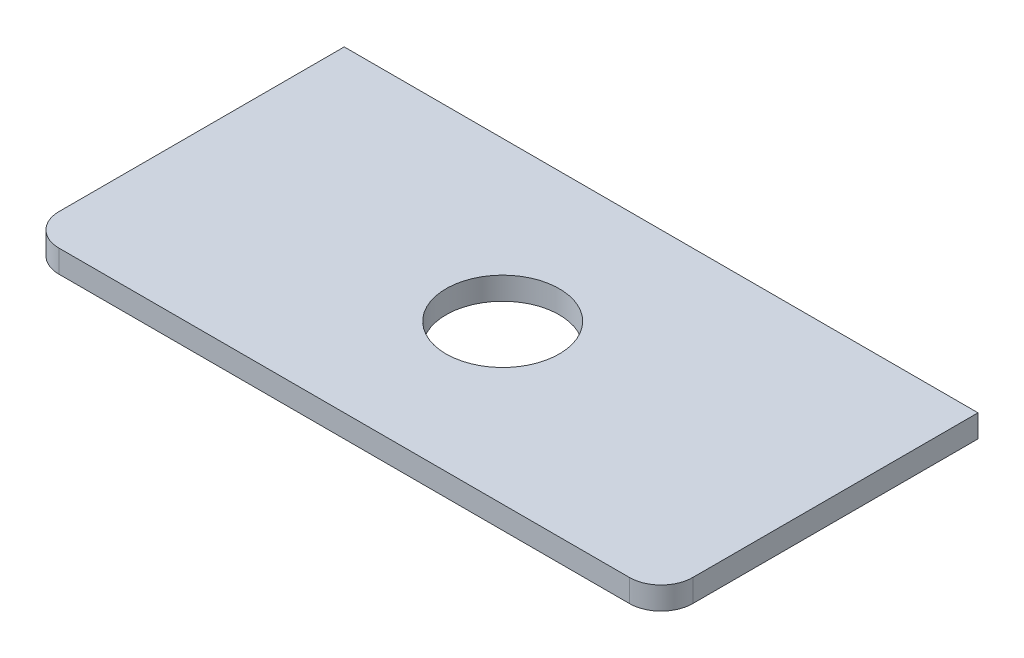
SolidWorks part; units mm, degrees
material "Plain Carbon Steel"
ref_plane "Front Plane" through (0, 0, 0) normal (0, 0, 1) x (1, 0, 0)
ref_plane "Top Plane" through (0, 0, 0) normal (0, 1, 0) x (1, 0, 0)
ref_plane "Right Plane" through (0, 0, 0) normal (1, 0, 0) x (0, 0, -1)
sketch "Sketch1" plane through (0, 0, 0) normal (0, 1, 0) x (1, 0, 0)
  line L1 (-140, -70) -> (140, -70)
  line L2 (-140, -70) -> (-140, 70)
  line L3 (-140, 70) -> (140, 70)
  line L4 (140, -70) -> (140, 70)
  line L5 (-140, -70) -> (140, 70) construction
  line L6 (-140, 70) -> (140, -70) construction
  point P0 (0, 0)
  dimension "D1" = 280
  dimension "D2" = 140
extrude "Boss-Extrude1" add sketch "Sketch1" along normal blind 10
fillet "Fillet1" radius 14 2 edges at (140, 5, 70) (-140, 5, 70)
sketch "Sketch2" plane through (0, 10, 0) normal (0, 1, 0) x (1, 0, 0)
  circle A0 centre (0, 0) radius 25
  dimension "D1" = 50
extrude "Cut-Extrude1" cut sketch "Sketch2" against normal blind 10
